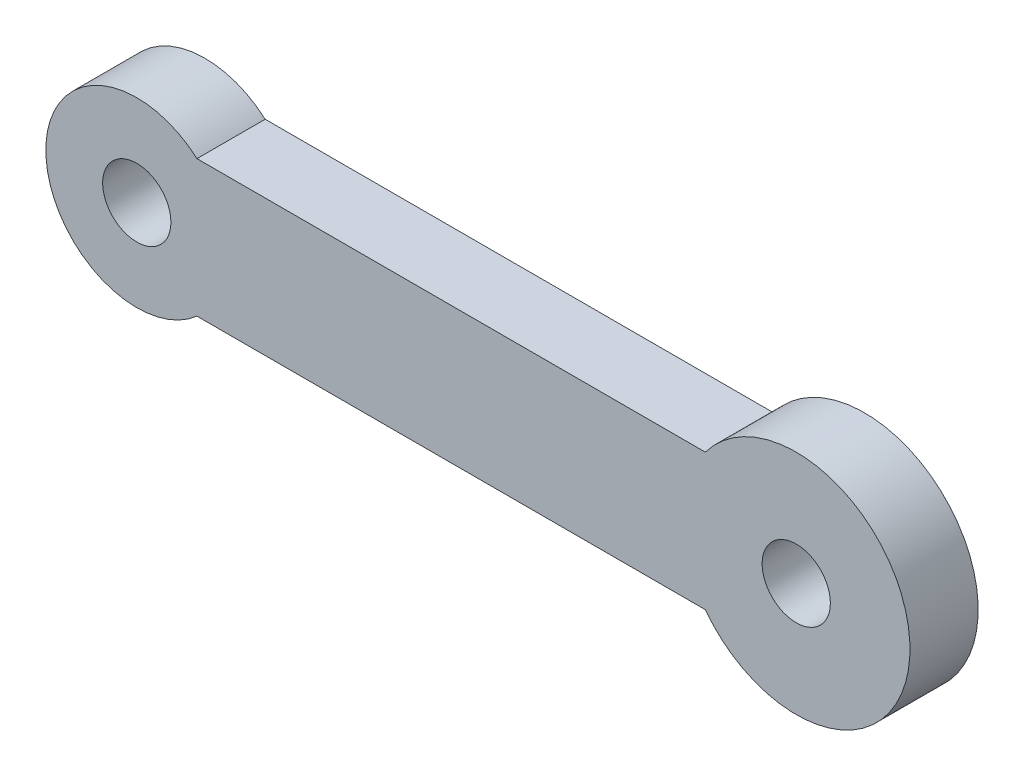
SolidWorks part; units mm, degrees
material "Acrílico (Impacto medio-alto)"
ref_plane "Alzado" through (0, 0, 0) normal (0, 0, 1) x (1, 0, 0)
ref_plane "Planta" through (0, 0, 0) normal (0, 1, 0) x (1, 0, 0)
ref_plane "Vista lateral" through (0, 0, 0) normal (1, 0, 0) x (0, 0, -1)
sketch "Croquis1" plane through (0, 0, 0) normal (0, 0, 1) x (1, 0, 0)
  line L1 (0, 3) -> (1.1127, 2.786)
  line L2 (0, -3) -> (29, -3)
  line L3 (0, -3) -> (0, 3)
  line L4 (0, 3) -> (29, 3)
  line L5 (29, -3) -> (29, 3)
  circle A0 centre (0, 0) radius 3
  circle A1 centre (0, 0) radius 4
  circle A3 centre (0, 0) radius 1.5
  circle A4 centre (29, 0) radius 1.5
  circle A6 centre (29, 0) radius 5
  point P9 (29, 0)
  dimension "D1" = 8
  dimension "D3" = 6
  dimension "D4" = 3
  dimension "D5" = 10
  dimension "D7" = 3
  dimension "D8" = 29
extrude "Saliente-Extruir1" add sketch "Croquis1" along normal blind 3
